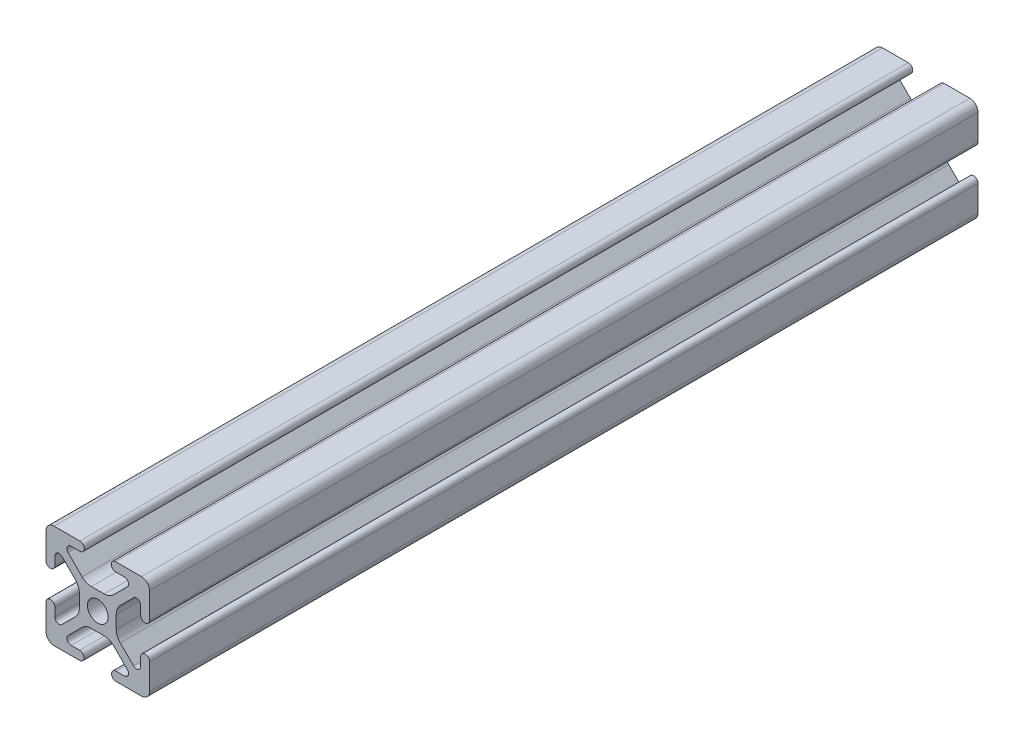
SolidWorks part; units mm, degrees
ref_plane "Front Plane" through (0, 0, 0) normal (0, 0, 1) x (1, 0, 0)
ref_plane "Top Plane" through (0, 0, 0) normal (0, 1, 0) x (1, 0, 0)
ref_plane "Right Plane" through (0, 0, 0) normal (1, 0, 0) x (0, 0, -1)
ref_plane "Plane1" through (0, 0, -25) normal (0, 0, -1) x (-1, 0, 0)
sketch "Sketch1" plane through (0, 0, -25) normal (0, 0, -1) x (-1, 0, 0)
  line L0 (12.5, 4.32) -> (12.5, 10.5371)
  line L1 (10.5371, 12.5) -> (4.32, 12.5)
  line L2 (4.32, 10.36) -> (6.42, 10.36)
  line L3 (7.1337, 8.6353) -> (3.7953, 5.3018)
  line L4 (1.5554, 4.375) -> (-1.5554, 4.375)
  line L5 (-3.7953, 5.3018) -> (-7.1337, 8.6353)
  line L6 (-6.42, 10.36) -> (-4.32, 10.36)
  line L7 (-4.32, 12.5) -> (-10.5371, 12.5)
  line L8 (-12.5, 10.5371) -> (-12.5, 4.32)
  line L9 (-10.36, 4.32) -> (-10.36, 6.3969)
  line L10 (-8.6363, 7.1116) -> (-5.4322, 3.9121)
  line L11 (-4.455, 1.5554) -> (-4.455, -1.5554)
  line L12 (-5.4322, -3.9121) -> (-8.6363, -7.1116)
  line L13 (-10.36, -6.3969) -> (-10.36, -4.32)
  line L14 (-12.5, -4.32) -> (-12.5, -10.5371)
  line L15 (-10.5371, -12.5) -> (-4.3879, -12.5)
  line L16 (-4.3879, -10.36) -> (-6.42, -10.36)
  line L17 (-7.1337, -8.6353) -> (-3.7953, -5.3018)
  line L18 (-1.5554, -4.375) -> (1.5554, -4.375)
  line L19 (3.7953, -5.3018) -> (7.1337, -8.6353)
  line L20 (6.42, -10.36) -> (4.3879, -10.36)
  line L21 (4.3879, -12.5) -> (10.5371, -12.5)
  line L22 (12.5, -10.5371) -> (12.5, -4.32)
  line L23 (10.36, -4.32) -> (10.36, -6.3969)
  line L24 (8.6363, -7.1116) -> (5.4322, -3.9121)
  line L25 (4.455, -1.5554) -> (4.455, 1.5554)
  line L26 (5.4322, 3.9121) -> (8.6363, 7.1116)
  line L27 (10.36, 6.3969) -> (10.36, 4.32)
  circle A0 centre (0, 0) radius 2.5
  arc A1 (12.5, 10.5371) -> (10.5371, 12.5) centre (10.5371, 10.5371) ccw
  arc A2 (4.32, 12.5) -> (4.32, 10.36) centre (4.32, 11.43) ccw
  arc A3 (6.42, 10.36) -> (7.1337, 8.6353) centre (6.42, 9.35) cw
  arc A4 (3.7953, 5.3018) -> (1.5554, 4.375) centre (1.5554, 7.545) cw
  arc A5 (-1.5554, 4.375) -> (-3.7953, 5.3018) centre (-1.5554, 7.545) cw
  arc A6 (-7.1337, 8.6353) -> (-6.42, 10.36) centre (-6.42, 9.35) cw
  arc A7 (-4.32, 10.36) -> (-4.32, 12.5) centre (-4.32, 11.43) ccw
  arc A8 (-10.5371, 12.5) -> (-12.5, 10.5371) centre (-10.5371, 10.5371) ccw
  arc A9 (-12.5, 4.32) -> (-10.36, 4.32) centre (-11.43, 4.32) ccw
  arc A10 (-10.36, 6.3969) -> (-8.6363, 7.1116) centre (-9.35, 6.3969) cw
  arc A11 (-5.4322, 3.9121) -> (-4.455, 1.5554) centre (-7.7855, 1.5554) cw
  arc A12 (-4.455, -1.5554) -> (-5.4322, -3.9121) centre (-7.7855, -1.5554) cw
  arc A13 (-8.6363, -7.1116) -> (-10.36, -6.3969) centre (-9.35, -6.3969) cw
  arc A14 (-10.36, -4.32) -> (-12.5, -4.32) centre (-11.43, -4.32) ccw
  arc A15 (-12.5, -10.5371) -> (-10.5371, -12.5) centre (-10.5371, -10.5371) ccw
  arc A16 (-4.3879, -12.5) -> (-4.3879, -10.36) centre (-4.3879, -11.43) ccw
  arc A17 (-6.42, -10.36) -> (-7.1337, -8.6353) centre (-6.42, -9.35) cw
  arc A18 (-3.7953, -5.3018) -> (-1.5554, -4.375) centre (-1.5554, -7.545) cw
  arc A19 (1.5554, -4.375) -> (3.7953, -5.3018) centre (1.5554, -7.545) cw
  arc A20 (7.1337, -8.6353) -> (6.42, -10.36) centre (6.42, -9.35) cw
  arc A21 (4.3879, -10.36) -> (4.3879, -12.5) centre (4.3879, -11.43) ccw
  arc A22 (10.5371, -12.5) -> (12.5, -10.5371) centre (10.5371, -10.5371) ccw
  arc A23 (12.5, -4.32) -> (10.36, -4.32) centre (11.43, -4.32) ccw
  arc A24 (10.36, -6.3969) -> (8.6363, -7.1116) centre (9.35, -6.3969) cw
  arc A25 (5.4322, -3.9121) -> (4.455, -1.5554) centre (7.7855, -1.5554) cw
  arc A26 (4.455, 1.5554) -> (5.4322, 3.9121) centre (7.7855, 1.5554) cw
  arc A27 (8.6363, 7.1116) -> (10.36, 6.3969) centre (9.35, 6.3969) cw
  arc A28 (10.36, 4.32) -> (12.5, 4.32) centre (11.43, 4.32) ccw
extrude "Boss-Extrude1" add sketch "Sketch1" against normal blind 200
